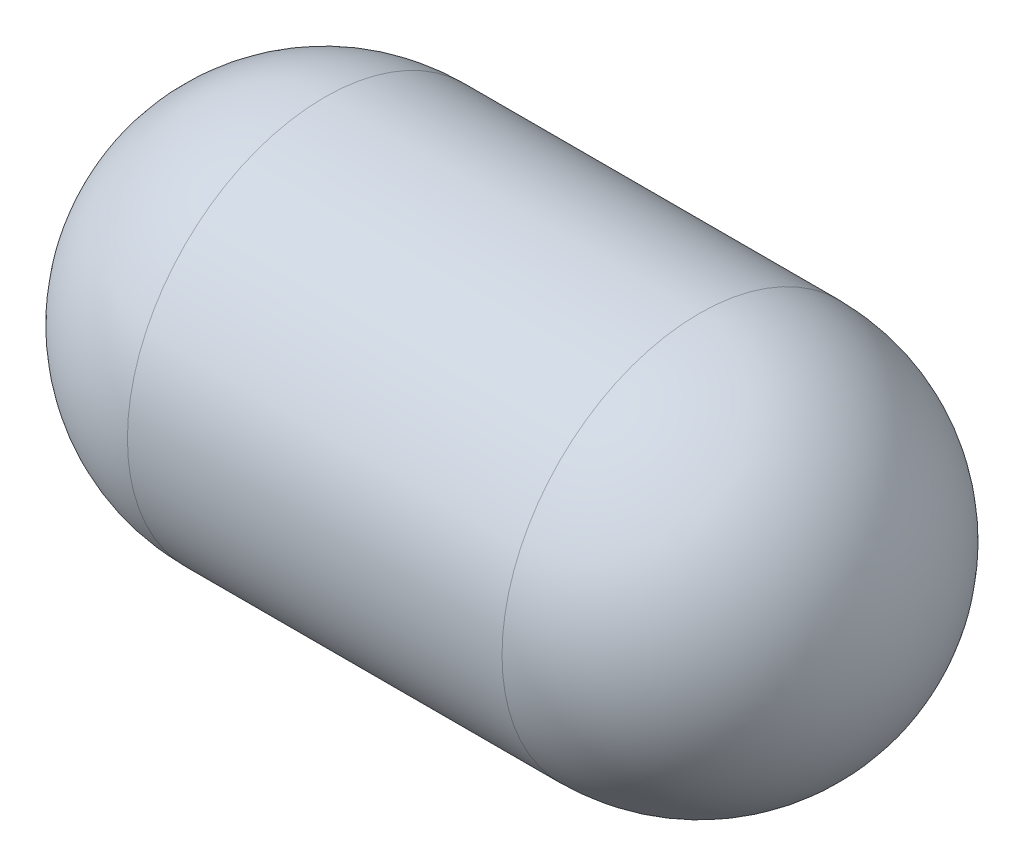
SolidWorks part; units mm, degrees
ref_plane "Front Plane" through (0, 0, 0) normal (0, 0, 1) x (1, 0, 0)
ref_plane "Top Plane" through (0, 0, 0) normal (0, 1, 0) x (1, 0, 0)
ref_plane "Right Plane" through (0, 0, 0) normal (1, 0, 0) x (0, 0, -1)
sketch "Sketch1" plane through (0, 0, 0) normal (0, 1, 0) x (1, 0, 0)
  line L0 (-1230.0658, 0) -> (1574.3372, 0) construction
  line L1 (0, 200) -> (380, 200)
  line L3 (-200, 0) -> (580, 0)
  arc A2 (580, 0) -> (380, 200) centre (380, 0) ccw
  arc A3 (0, 200) -> (-200, 0) centre (0, 0) ccw
  dimension "D1" = 380
  dimension "D2" = 200
revolve "Revolve4" add sketch "Sketch1" angle 360 about L0
shell "Shell1" thickness 10
